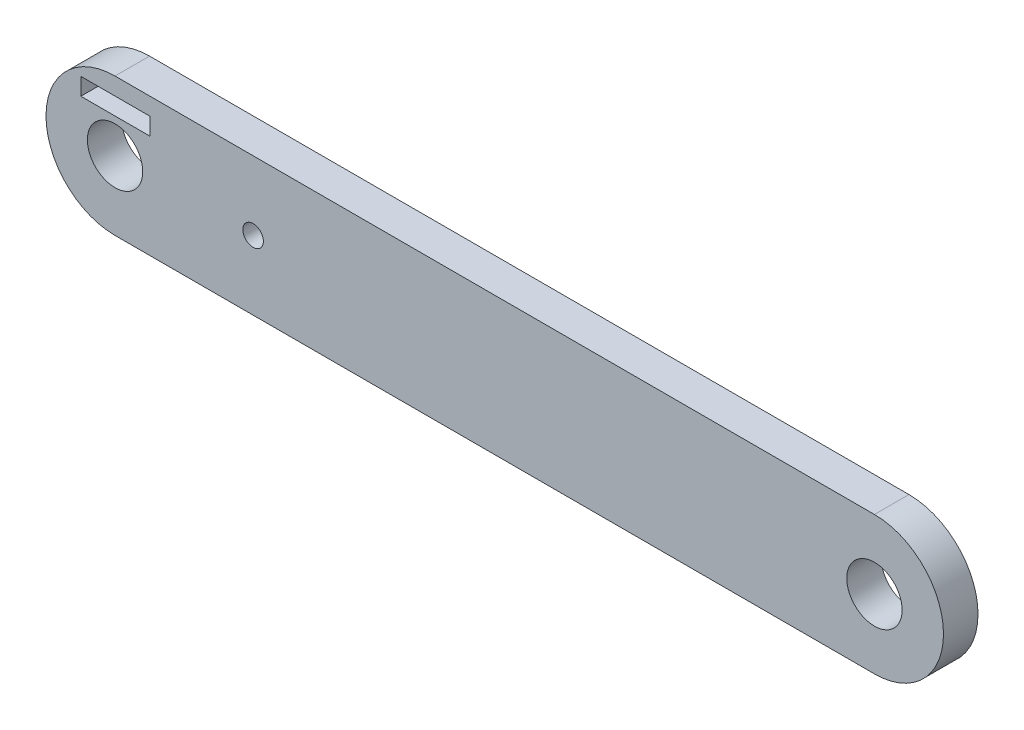
SolidWorks part; units mm, degrees
ref_plane "Front Plane" through (0, 0, 0) normal (0, 0, 1) x (1, 0, 0)
ref_plane "Top Plane" through (0, 0, 0) normal (0, 1, 0) x (1, 0, 0)
ref_plane "Right Plane" through (0, 0, 0) normal (1, 0, 0) x (0, 0, -1)
sketch "Sketch1" plane through (0, 0, 0) normal (0, 0, 1) x (1, 0, 0)
  line L0 (0, 10) -> (110, 10)
  line L1 (0, -10) -> (110, -10)
  circle A0 centre (0, 0) radius 10
  circle A2 centre (0, 0) radius 4.01
  circle A3 centre (110, 0) radius 4.01
  circle A4 centre (110, 0) radius 10
  dimension "D1" = 20
  dimension "D2" = 20
  dimension "D4" = 8.02
  dimension "D5" = 8.02
  dimension "D3" = 110
  dimension "D6" = 110
extrude "Boss-Extrude1" add sketch "Sketch1" along normal blind 5
sketch "Sketch2" plane through (0, 0, 0) normal (0, 0, -1) x (-1, 0, 0)
  circle A2 centre (-20, 0) radius 1.49
  dimension "D1" = 20
  dimension "D2" = 2.98
sketch "Sketch4" plane through (0, 0, 0) normal (0, 0, -1) x (-1, 0, 0)
  line L2 (4.9531, 4.9852) -> (-5.0469, 4.9852)
  line L8 (-5.0469, 4.9852) -> (-5.0469, 7.4852)
  line L9 (-5.0469, 7.4852) -> (4.9531, 7.4852)
  line L10 (4.9531, 4.9852) -> (4.9531, 7.4852)
  dimension "D1" = 2.5
extrude "Cut-Extrude1" cut sketch "Sketch2" against normal up to next
extrude "Cut-Extrude2" cut sketch "Sketch4" against normal blind 10
